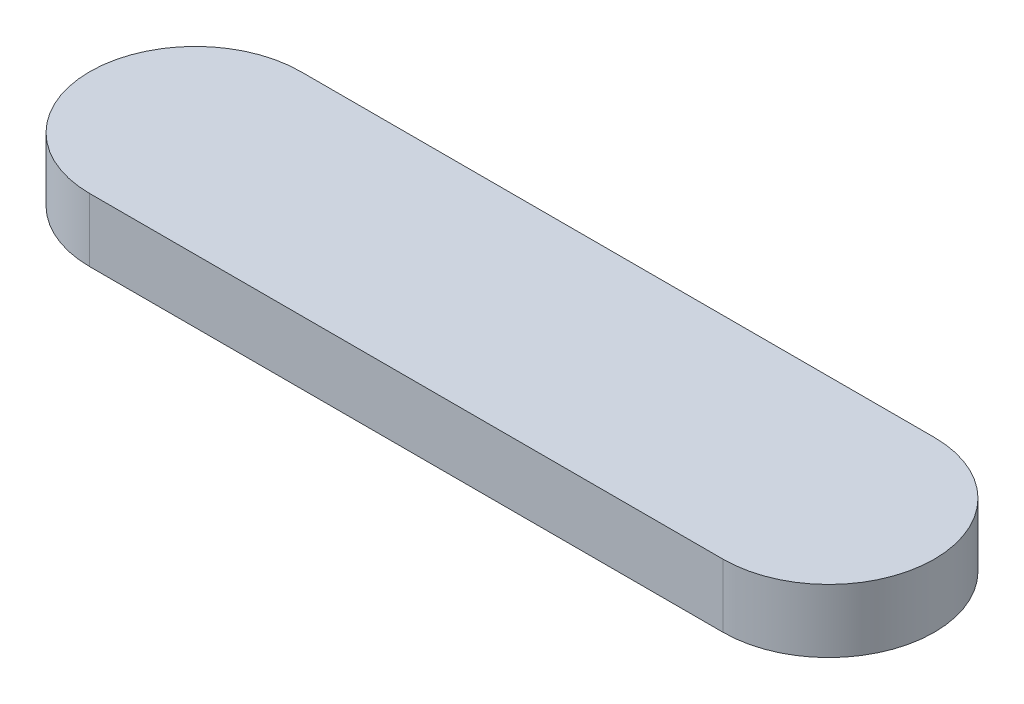
SolidWorks part; units mm, degrees
ref_plane "前视基准面" through (0, 0, 0) normal (0, 0, 1) x (1, 0, 0)
ref_plane "上视基准面" through (0, 0, 0) normal (0, 1, 0) x (1, 0, 0)
ref_plane "右视基准面" through (0, 0, 0) normal (1, 0, 0) x (0, 0, -1)
other "Configuration Table"
sketch "草图1" plane through (0, 0, 0) normal (0, 1, 0) x (1, 0, 0)
  line L0 (0, 0) -> (30, 0) construction
  line L5 (0, 5) -> (30, 5)
  line L6 (0, -5) -> (30, -5)
  arc A0 (0, 5) -> (0, -5) centre (0, 0) ccw
  arc A1 (30, -5) -> (30, 5) centre (30, 0) ccw
  point P2 (15, 0)
  dimension "D1" = 30
  dimension "D2" = 10
extrude "凸台-拉伸1" add sketch "草图1" along normal blind 3
